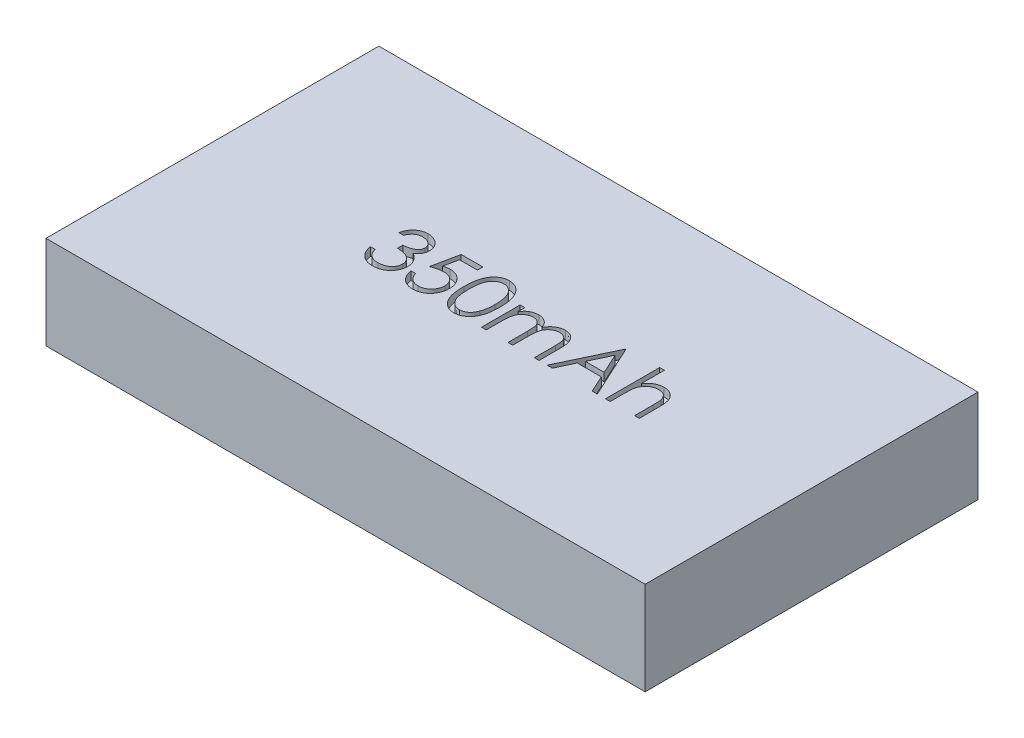
SolidWorks part; units mm, degrees
ref_plane "Front Plane" through (0, 0, 0) normal (0, 0, 1) x (1, 0, 0)
ref_plane "Top Plane" through (0, 0, 0) normal (0, 1, 0) x (1, 0, 0)
ref_plane "Right Plane" through (0, 0, 0) normal (1, 0, 0) x (0, 0, -1)
sketch "Sketch1" plane through (0, 0, 0) normal (0, 1, 0) x (1, 0, 0)
  line L1 (0, 0) -> (36, 0)
  line L2 (0, 0) -> (0, 20)
  line L3 (0, 20) -> (36, 20)
  line L4 (36, 0) -> (36, 20)
  dimension "D1" = 36
  dimension "D2" = 20
extrude "Boss-Extrude1" add sketch "Sketch1" along normal blind 5.6
sketch "Sketch2" plane through (0, 5.6, 0) normal (0, 1, 0) x (1, 0, 0)
  text T0 "350mAh"
extrude "Cut-Extrude1" cut sketch "Sketch2" against normal blind 0.5
